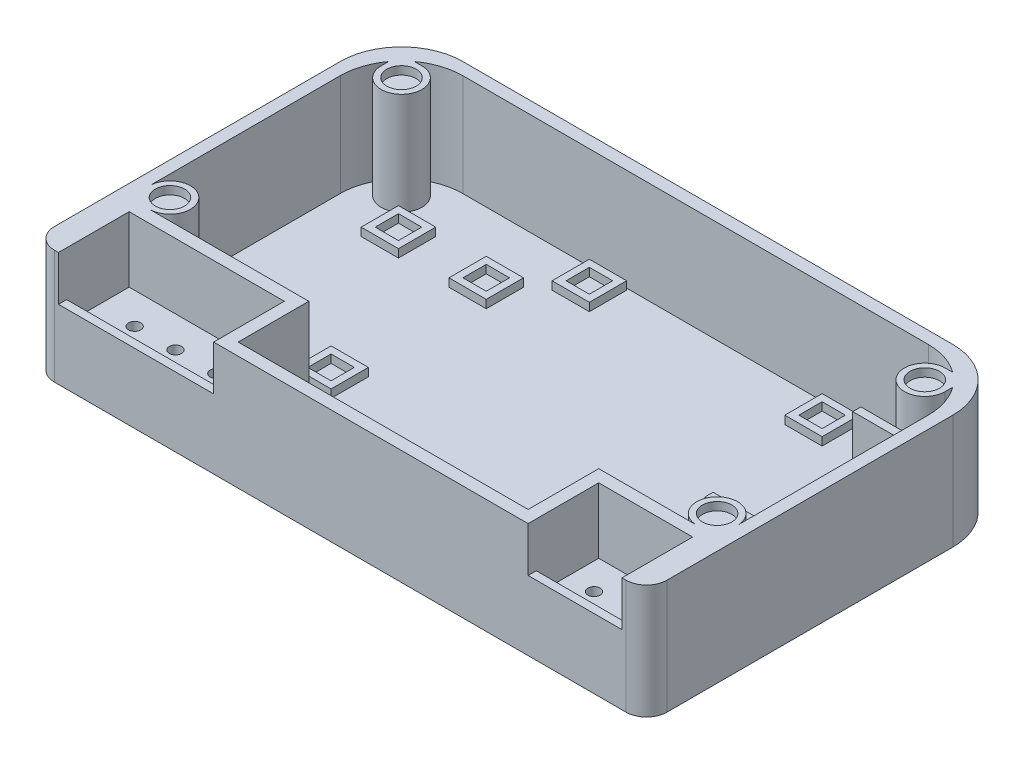
SolidWorks part; units mm, degrees
ref_plane "Alzado" through (0, 0, 0) normal (0, 0, 1) x (1, 0, 0)
ref_plane "Planta" through (0, 0, 0) normal (0, 1, 0) x (1, 0, 0)
ref_plane "Vista lateral" through (0, 0, 0) normal (1, 0, 0) x (0, 0, -1)
sketch "Croquis1" plane through (0, 0, 0) normal (0, 1, 0) x (1, 0, 0)
  line L1 (-75, -45) -> (75, -45)
  line L2 (-75, -45) -> (-75, 45)
  line L3 (-75, 45) -> (75, 45)
  line L4 (75, -45) -> (75, 45)
  line L5 (-75, -45) -> (75, 45) construction
  line L6 (-75, 45) -> (75, -45) construction
  point P0 (0, 0)
  dimension "D1" = 90
  dimension "D2" = 150
extrude "Saliente-Extruir1" add sketch "Croquis1" along normal blind 3
sketch "Croquis2" plane through (0, 3, 0) normal (0, 1, 0) x (1, 0, 0)
  line L0 (-75, -45) -> (-75, 45)
  line L1 (-75, 45) -> (75, 45)
  line L3 (75, -45) -> (69, -45)
  line L4 (-75, -45) -> (75, -45) construction
  line L5 (69, -45) -> (69, -27.7)
  line L6 (69, -27.7) -> (46, -27.7)
  line L7 (46, -27.7) -> (46, -45)
  line L8 (46, -45) -> (-31, -45)
  line L9 (-31, -45) -> (-31, -27.7)
  line L10 (-31, -27.7) -> (-69, -27.7)
  line L11 (-69, -27.7) -> (-69, -45)
  line L12 (-69, -45) -> (-75, -45)
  line L14 (-72, 42) -> (72, 42)
  line L18 (72, -24.7) -> (43, -24.7)
  line L19 (43, -24.7) -> (43, -42)
  line L20 (43, -42) -> (-28, -42)
  line L21 (-28, -42) -> (-28, -24.7)
  line L22 (-28, -24.7) -> (-72, -24.7)
  line L25 (-72, -24.7) -> (-72, -42) construction
  line L26 (-72, -42) -> (-72, -42) construction
  line L27 (-72, -42) -> (-72, 42) construction
  line L28 (-72, 42) -> (-72, -24.7)
  line L29 (72, 42) -> (72, -24.7)
  line L30 (72, 42) -> (72, -42) construction
  line L31 (72, -42) -> (72, -24.7) construction
  line L32 (75, 45) -> (75, -45) construction
  line L33 (72, -42) -> (72, -42) construction
  line L34 (75, 45) -> (75, -45)
  dimension "D1" = 17.3
  dimension "D2" = 6
  dimension "D3" = 23
  dimension "D4" = 38
  dimension "D5" = 3
extrude "Saliente-Extruir2" add sketch "Croquis2" along normal blind 25
sketch "Croquis3" plane through (0, 3, 0) normal (0, 1, 0) x (1, 0, 0)
  line L0 (-31, -27.7) -> (-31, -45) construction
  line L1 (-69, -45) -> (-31, -45)
  line L2 (-69, -45) -> (-69, -43)
  line L3 (-69, -43) -> (-31, -43)
  line L4 (-31, -45) -> (-31, -43)
  line L5 (69, -27.7) -> (69, -45) construction
  line L6 (46, -45) -> (69, -45)
  line L7 (46, -45) -> (46, -43)
  line L8 (46, -43) -> (69, -43)
  line L9 (69, -45) -> (69, -43)
  dimension "D1" = 2
extrude "Saliente-Extruir3" add sketch "Croquis3" along normal blind 14
sketch "Croquis4" plane through (0, 3, 0) normal (0, 1, 0) x (1, 0, 0)
  line L0 (62.5, -35.35) -> (69, -35.35) construction
  line L1 (52.5, -35.35) -> (46, -35.35) construction
  line L2 (-50, -35.35) -> (-50, -27.7) construction
  line L4 (-69, -43) -> (-31, -43)
  line L5 (-31, -43) -> (-31, -27.7)
  line L6 (-31, -27.7) -> (-69, -27.7)
  line L7 (-69, -27.7) -> (-69, -43)
  line L8 (-69, -43) -> (-31, -43)
  line L9 (-31, -43) -> (-31, -27.7)
  line L10 (-31, -27.7) -> (-69, -27.7)
  line L11 (-69, -27.7) -> (-69, -43)
  line L12 (46, -43) -> (69, -43)
  line L13 (69, -43) -> (69, -27.7)
  line L14 (69, -27.7) -> (46, -27.7)
  line L15 (46, -27.7) -> (46, -43)
  line L16 (46, -43) -> (69, -43)
  line L17 (69, -43) -> (69, -27.7)
  line L18 (69, -27.7) -> (46, -27.7)
  line L19 (46, -27.7) -> (46, -43)
  circle A0 centre (62.5, -35.35) radius 1.5
  circle A1 centre (52.5, -35.35) radius 1.5
  circle A2 centre (-50, -35.35) radius 1.5
  circle A3 centre (-40, -35.35) radius 1.5
  circle A4 centre (-60, -35.35) radius 1.5
  dimension "D4" = 3
  dimension "D3" = 10
  dimension "D5" = 10
  dimension "D1" = 0
  dimension "D2" = 0
extrude "Saliente-Extruir4" add sketch "Croquis4" along normal blind 3 from offset 6
sketch "Croquis5" plane through (0, 0, 27.7) normal (0, 0, 1) x (1, 0, 0)
  line L0 (-69, 3) -> (-31, 3) construction
  line L1 (-60, 3) -> (-40, 3)
  line L2 (-60, 3) -> (-60, 9)
  line L3 (-60, 9) -> (-40, 9)
  line L4 (-40, 3) -> (-40, 9)
  line L5 (-31, 9) -> (-69, 9) construction
  line L6 (46, 3) -> (69, 3) construction
  line L7 (52.5, 3) -> (62.5, 3)
  line L8 (52.5, 3) -> (52.5, 9)
  line L9 (52.5, 9) -> (62.5, 9)
  line L10 (62.5, 3) -> (62.5, 9)
  line L11 (69, 9) -> (46, 9) construction
  line L12 (-50, 9) -> (-50, 3) construction
  line L13 (57.5, 9) -> (57.5, 3) construction
  dimension "D1" = 20
  dimension "D2" = 10
extrude "Cortar-Extruir1" cut sketch "Croquis5" against normal up to next
fillet "Redondeo1" radius 15 4 edges at (-75, 14, -45) (-72, 15.5, -42) (72, 15.5, -42) (75, 14, -45)
fillet "Redondeo2" radius 5 2 edges at (75, 14, 45) (-75, 14, 45)
sketch "Croquis6" plane through (0, 3, 0) normal (0, 1, 0) x (1, 0, 0)
  line L0 (-57, 42) -> (-57, 27) construction
  line L1 (-57, 27) -> (-64.0711, 34.0711) construction
  line L2 (-64.0711, 39.0711) -> (-65.9045, 39.0711)
  line L3 (-69.0711, 34.0711) -> (-69.0711, 35.9045)
  line L4 (-72, 27) -> (-72, -24.7) construction
  line L5 (-72, -24.7) -> (-28, -24.7) construction
  line L6 (-67, -24.7) -> (-72, -24.7)
  line L7 (-72, -24.7) -> (-72, -19.7)
  line L8 (0, 0) -> (0, 42) construction
  line L9 (57, 42) -> (-57, 42) construction
  line L10 (57, 27) -> (64.0711, 34.0711) construction
  line L11 (57, 42) -> (57, 27) construction
  line L12 (72, -24.7) -> (72, -19.7)
  line L13 (67, -24.7) -> (72, -24.7)
  line L14 (69.0711, 34.0711) -> (69.0711, 35.9045)
  line L15 (64.0711, 39.0711) -> (65.9045, 39.0711)
  arc A0 (-67, -24.7) -> (-72, -19.7) centre (-67, -19.7) ccw
  arc A1 (-69.0711, 34.0711) -> (-64.0711, 39.0711) centre (-64.0711, 34.0711) ccw
  arc A4 (-57, 42) -> (-72, 27) centre (-57, 27) ccw construction
  arc A5 (-57, 42) -> (-72, 27) centre (-57, 27) ccw construction
  arc A6 (-69.0711, 35.9045) -> (-65.9045, 39.0711) centre (-57, 27) cw
  arc A7 (69.0711, 35.9045) -> (65.9045, 39.0711) centre (57, 27) ccw
  arc A8 (69.0711, 34.0711) -> (64.0711, 39.0711) centre (64.0711, 34.0711) cw
  arc A9 (67, -24.7) -> (72, -19.7) centre (67, -19.7) cw
  dimension "D1" = 10
  dimension "D2" = 45
extrude "Saliente-Extruir5" add sketch "Croquis6" along normal up to surface (25 mm away) up to face at (1.875, 28, 19.1661)
sketch "Croquis7" plane through (0, 28, 0) normal (0, 1, 0) x (1, 0, 0)
  circle A0 centre (-64.0711, 34.0711) radius 3.6
  circle A1 centre (64.0711, 34.0711) radius 3.6
  circle A2 centre (67, -19.7) radius 3.6
  circle A3 centre (-67, -19.7) radius 3.6
  dimension "D1" = 7.2
extrude "Cortar-Extruir2" cut sketch "Croquis7" against normal blind 2
sketch "Croquis8" plane through (0, 3, 0) normal (0, 1, 0) x (1, 0, 0)
  line L0 (-21, 37) -> (36, 37) construction
  line L1 (36, 37) -> (36, -34) construction
  line L2 (-28, -42) -> (43, -42) construction
  line L3 (-38.8149, 20.4351) -> (-38.8149, 29.5649)
  line L4 (57, 42) -> (-57, 42) construction
  line L5 (7.5, 37) -> (7.5, 1.5) construction
  line L6 (-18.15, 39.85) -> (-23.85, 39.85)
  line L7 (-18.15, 39.85) -> (-18.15, 34.15)
  line L8 (-18.15, 34.15) -> (-23.85, 34.15)
  line L9 (-23.85, 39.85) -> (-23.85, 34.15)
  line L10 (-18.15, 39.85) -> (-23.85, 34.15) construction
  line L11 (-18.15, 34.15) -> (-23.85, 39.85) construction
  line L12 (7.5, 1.5) -> (36, 1.5) construction
  line L13 (33.15, 34.15) -> (38.85, 39.85) construction
  line L14 (33.15, 39.85) -> (38.85, 34.15) construction
  line L15 (38.85, 39.85) -> (38.85, 34.15)
  line L16 (33.15, 34.15) -> (38.85, 34.15)
  line L17 (33.15, 39.85) -> (33.15, 34.15)
  line L18 (33.15, 39.85) -> (38.85, 39.85)
  line L19 (33.15, -36.85) -> (38.85, -31.15) construction
  line L20 (33.15, -31.15) -> (38.85, -36.85) construction
  line L21 (-18.15, -31.15) -> (-23.85, -36.85) construction
  line L22 (-18.15, -36.85) -> (-23.85, -31.15) construction
  line L23 (-55.75, 25) -> (-34.25, 25) construction
  line L24 (33.15, -36.85) -> (38.85, -36.85)
  line L25 (33.15, -36.85) -> (33.15, -31.15)
  line L26 (33.15, -31.15) -> (38.85, -31.15)
  line L27 (38.85, -36.85) -> (38.85, -31.15)
  line L28 (-23.85, -36.85) -> (-23.85, -31.15)
  line L29 (-18.15, -31.15) -> (-23.85, -31.15)
  line L30 (-18.15, -36.85) -> (-18.15, -31.15)
  line L31 (-18.15, -36.85) -> (-23.85, -36.85)
  line L32 (-34.25, 25) -> (-34.25, -13) construction
  line L33 (-45, 25) -> (-45, 6) construction
  line L34 (-45, 6) -> (-34.25, 6) construction
  line L35 (-72, 27) -> (-72, -19.7) construction
  line L36 (-37.1, 27.85) -> (-31.4, 22.15) construction
  line L37 (-52.9, 22.15) -> (-58.6, 22.15)
  line L38 (-52.9, 22.15) -> (-52.9, 27.85)
  line L39 (-52.9, 27.85) -> (-58.6, 27.85)
  line L40 (-58.6, 22.15) -> (-58.6, 27.85)
  line L41 (-52.9, 22.15) -> (-58.6, 27.85) construction
  line L42 (-52.9, 27.85) -> (-58.6, 22.15) construction
  line L43 (-37.1, 22.15) -> (-31.4, 27.85) construction
  line L44 (-31.4, 22.15) -> (-31.4, 27.85)
  line L45 (-37.1, 27.85) -> (-31.4, 27.85)
  line L46 (-37.1, 22.15) -> (-37.1, 27.85)
  line L47 (-37.1, 22.15) -> (-31.4, 22.15)
  line L48 (-37.1, -10.15) -> (-31.4, -15.85) construction
  line L49 (-52.9, -15.85) -> (-58.6, -10.15) construction
  line L50 (-52.9, -10.15) -> (-58.6, -15.85) construction
  line L51 (-37.1, -15.85) -> (-31.4, -10.15) construction
  line L52 (-55.75, -13) -> (-34.25, -13) construction
  line L53 (-37.1, -10.15) -> (-31.4, -10.15)
  line L54 (-37.1, -10.15) -> (-37.1, -15.85)
  line L55 (-37.1, -15.85) -> (-31.4, -15.85)
  line L56 (-31.4, -10.15) -> (-31.4, -15.85)
  line L57 (-58.6, -10.15) -> (-58.6, -15.85)
  line L58 (-52.9, -15.85) -> (-58.6, -15.85)
  line L59 (-52.9, -10.15) -> (-52.9, -15.85)
  line L60 (-52.9, -10.15) -> (-58.6, -10.15)
  line L61 (-38.8149, 20.4351) -> (-29.6851, 20.4351)
  line L62 (-51.1851, 20.4351) -> (-60.3149, 20.4351)
  line L63 (-51.1851, 20.4351) -> (-51.1851, 29.5649)
  line L64 (-51.1851, 29.5649) -> (-60.3149, 29.5649)
  line L65 (-60.3149, 20.4351) -> (-60.3149, 29.5649)
  line L66 (-51.1851, 20.4351) -> (-60.3149, 29.5649) construction
  line L67 (-51.1851, 29.5649) -> (-60.3149, 20.4351) construction
  line L68 (-29.6851, 20.4351) -> (-29.6851, 29.5649)
  line L69 (-38.8149, 29.5649) -> (-29.6851, 29.5649)
  line L70 (-29.6851, -8.4351) -> (-29.6851, -17.5649)
  line L71 (-38.8149, -8.4351) -> (-29.6851, -8.4351)
  line L72 (-38.8149, -8.4351) -> (-38.8149, -17.5649)
  line L73 (-38.8149, -17.5649) -> (-29.6851, -17.5649)
  line L74 (-51.1851, -17.5649) -> (-60.3149, -17.5649)
  line L75 (-60.3149, -8.4351) -> (-60.3149, -17.5649)
  line L76 (-51.1851, -8.4351) -> (-60.3149, -8.4351)
  line L77 (-51.1851, -8.4351) -> (-51.1851, -17.5649)
  line L78 (40.5649, 41.5649) -> (31.4351, 41.5649)
  line L79 (-25.5649, 41.5649) -> (-16.4351, 41.5649)
  line L80 (-25.5649, 41.5649) -> (-25.5649, 32.4351)
  line L81 (-25.5649, 32.4351) -> (-16.4351, 32.4351)
  line L82 (-16.4351, 41.5649) -> (-16.4351, 32.4351)
  line L83 (-25.5649, 41.5649) -> (-16.4351, 32.4351) construction
  line L84 (-25.5649, 32.4351) -> (-16.4351, 41.5649) construction
  line L85 (40.5649, 41.5649) -> (40.5649, 32.4351)
  line L86 (40.5649, 32.4351) -> (31.4351, 32.4351)
  line L87 (31.4351, 41.5649) -> (31.4351, 32.4351)
  line L88 (-25.5649, -38.5649) -> (-16.4351, -38.5649)
  line L89 (-25.5649, -38.5649) -> (-25.5649, -29.4351)
  line L90 (-25.5649, -29.4351) -> (-16.4351, -29.4351)
  line L91 (-16.4351, -38.5649) -> (-16.4351, -29.4351)
  line L92 (40.5649, -38.5649) -> (40.5649, -29.4351)
  line L93 (40.5649, -38.5649) -> (31.4351, -38.5649)
  line L94 (31.4351, -38.5649) -> (31.4351, -29.4351)
  line L95 (40.5649, -29.4351) -> (31.4351, -29.4351)
  point P7 (7.5, -42)
  point P8 (7.5, 37)
  point P62 (-58.6, 25)
  dimension "D1" = 57
  dimension "D2" = 71
  dimension "D3" = 5
  dimension "D4" = 5.7
  dimension "D5" = 38
  dimension "D6" = 21.5
  dimension "D7" = 27
  dimension "D8" = 17
  dimension "D9" = 1.7149
extrude "Saliente-Extruir6" add sketch "Croquis8" along normal blind 2
sketch "Croquis9" plane through (0, 3, 0) normal (0, 1, 0) x (1, 0, 0)
  line L0 (72, -12.7) -> (57, -12.7)
  line L1 (72, -12.7) -> (72, -10.7)
  line L2 (72, -10.7) -> (57, -10.7)
  line L3 (57, -12.7) -> (57, -10.7)
  line L4 (72, 23.5) -> (57, 23.5)
  line L5 (72, 23.5) -> (72, 25.5)
  line L6 (72, 25.5) -> (57, 25.5)
  line L7 (57, 23.5) -> (57, 25.5)
  line L9 (72, -19.7) -> (72, 27) construction
  point P8 (0, 0)
  point P9 (72, -13.06)
  point P12 (72, 22.945)
  dimension "D1" = 34.2
  dimension "D2" = 15
  dimension "D3" = 2
  dimension "D4" = 7
extrude "Saliente-Extruir7" add sketch "Croquis9" along normal blind 20
